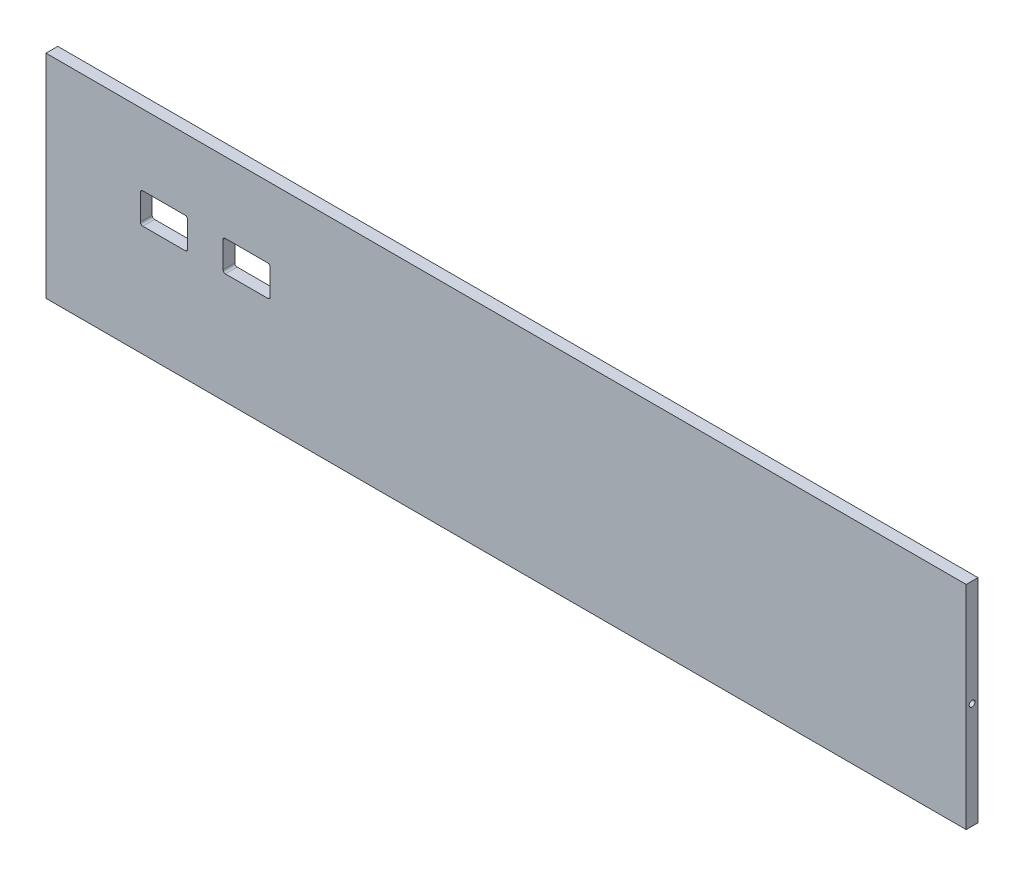
SolidWorks part; units mm, degrees
ref_plane "Front Plane" through (0, 0, 0) normal (0, 0, 1) x (1, 0, 0)
ref_plane "Top Plane" through (0, 0, 0) normal (0, 1, 0) x (1, 0, 0)
ref_plane "Right Plane" through (0, 0, 0) normal (1, 0, 0) x (0, 0, -1)
sketch "Sketch1" plane through (0, 0, 0) normal (0, 0, 1) x (1, 0, 0)
  line L1 (0, 0) -> (390, 0)
  line L2 (0, 0) -> (0, 90)
  line L3 (0, 90) -> (390, 90)
  line L4 (390, 0) -> (390, 90)
  line L5 (41, 60) -> (59, 60)
  line L6 (40, 59) -> (40, 48)
  line L7 (41, 47) -> (59, 47)
  line L8 (60, 59) -> (60, 48)
  line L9 (76, 60) -> (94, 60)
  line L10 (75, 59) -> (75, 48)
  line L11 (76, 47) -> (94, 47)
  line L12 (95, 59) -> (95, 48)
  arc A0 (94, 47) -> (95, 48) centre (94, 48) ccw
  arc A1 (94, 60) -> (95, 59) centre (94, 59) cw
  arc A2 (76, 60) -> (75, 59) centre (76, 59) ccw
  arc A3 (59, 60) -> (60, 59) centre (59, 59) cw
  arc A4 (59, 47) -> (60, 48) centre (59, 48) ccw
  arc A5 (75, 48) -> (76, 47) centre (76, 48) ccw
  arc A6 (40, 48) -> (41, 47) centre (41, 48) ccw
  arc A7 (40, 59) -> (41, 60) centre (41, 59) cw
  point P17 (95, 60)
  point P20 (75, 60)
  point P23 (60, 60)
  point P28 (75, 47)
  point P31 (40, 47)
  point P34 (40, 60)
  dimension "D10" = 1
  dimension "D1" = 390
  dimension "D2" = 90
  dimension "D3" = 20
  dimension "D4" = 20
  dimension "D5" = 13
  dimension "D6" = 13
  dimension "D7" = 40
  dimension "D8" = 15
  dimension "D9" = 30
extrude "Boss-Extrude2" add sketch "Sketch1" along normal blind 5
sketch "Sketch2" plane through (0, 0, 0) normal (-1, 0, 0) x (0, 0, 1)
  line L0 (5, 90) -> (0, 90) construction
  line L1 (0, 90) -> (0, 0) construction
  circle A0 centre (2.5, 45) radius 1.25
  dimension "D1" = 45
  dimension "D2" = 2.5
extrude "Cut-Extrude1" cut sketch "Sketch2" against normal blind 15
sketch "Sketch3" plane through (390, 0, 0) normal (1, 0, 0) x (0, 0, -1)
  line L0 (-5, 0) -> (-5, 90) construction
  line L1 (-5, 90) -> (0, 90) construction
  circle A0 centre (-2.5, 45) radius 1.25
  dimension "D1" = 2.5
  dimension "D2" = 45
extrude "Cut-Extrude2" cut sketch "Sketch3" against normal blind 15
sketch "Sketch4" plane through (0, 0, 0) normal (0, -1, 0) x (1, 0, 0)
  line L0 (390, 5) -> (390, 0) construction
  line L1 (0, 5) -> (390, 5) construction
  line L2 (0, 5) -> (0, 0) construction
  circle A0 centre (35, 2.5) radius 1.25
  circle A1 centre (355, 2.5) radius 1.25
  dimension "D1" = 35
  dimension "D2" = 2.5
  dimension "D3" = 2.5
  dimension "D4" = 35
extrude "Cut-Extrude3" cut sketch "Sketch4" against normal blind 15
